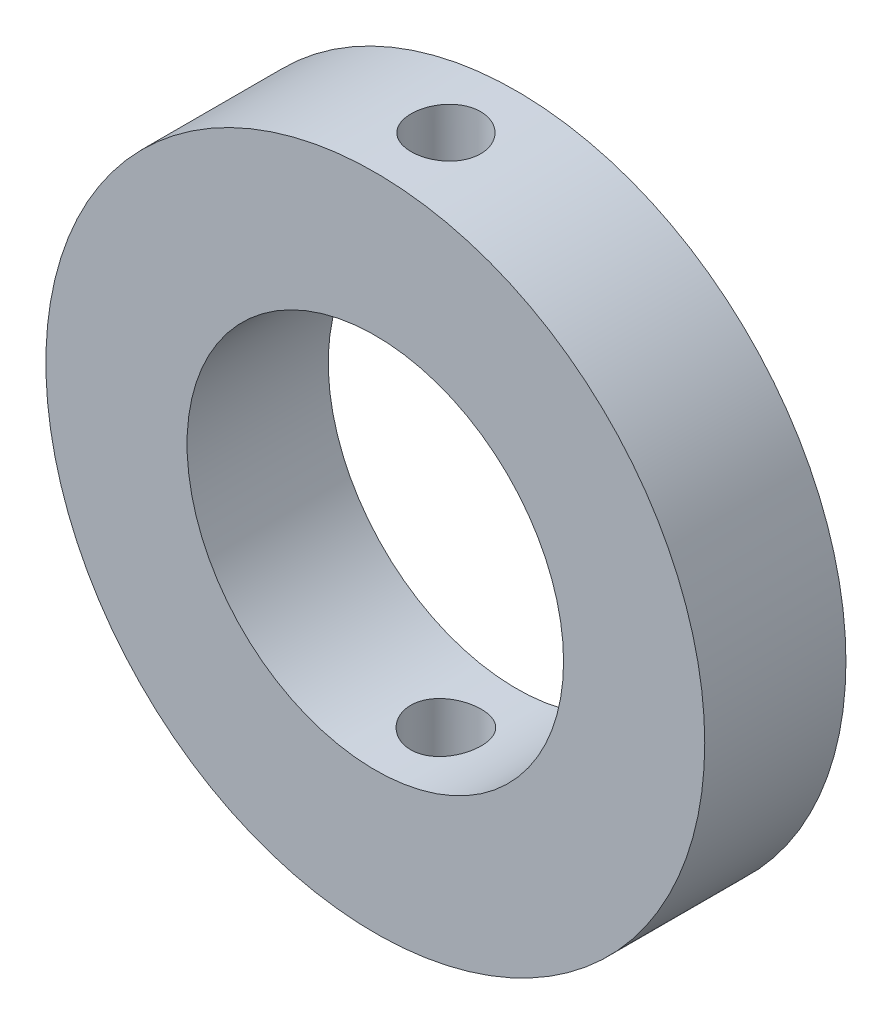
SolidWorks part; units mm, degrees
ref_plane "Front" through (0, 0, 0) normal (0, 0, 1) x (1, 0, 0)
ref_plane "Top" through (0, 0, 0) normal (0, 1, 0) x (1, 0, 0)
ref_plane "Right" through (0, 0, 0) normal (1, 0, 0) x (0, 0, -1)
sketch "Sketch1" plane through (0, 0, 0) normal (0, 0, 1) x (1, 0, 0)
  circle A0 centre (0, 0) radius 11.1125
  dimension "D1" = 22.225
extrude "Boss-Extrude1" add sketch "Sketch1" along normal blind 4.7625
sketch "Sketch2" plane through (0, 0, 4.7625) normal (0, 0, 1) x (1, 0, 0)
  circle A0 centre (0, 0) radius 6.35
  dimension "D1" = 12.7
extrude "Cut-Extrude1" cut sketch "Sketch2" against normal through all
ref_plane "Plane1" through (0, 0, 2.3813) normal (0, 0, 1) x (1, 0, 0)
sketch "Sketch3" plane through (0, 0, 2.3813) normal (0, 0, 1) x (1, 0, 0)
  line L0 (1.1938, -11.2556) -> (1.172, 10.9694) construction
  line L1 (1.1937, -11.1125) -> (1.1719, 11.1125)
  line L2 (1.1719, 11.1125) -> (0, 11.1125)
  line L3 (0, 11.1125) -> (0, -11.1125)
  line L4 (0, -11.1125) -> (1.1937, -11.1125)
  circle A0 centre (0, 0) radius 11.1125 construction
revolve "Cut-Revolve1" cut sketch "Sketch3" angle 360 about L3
